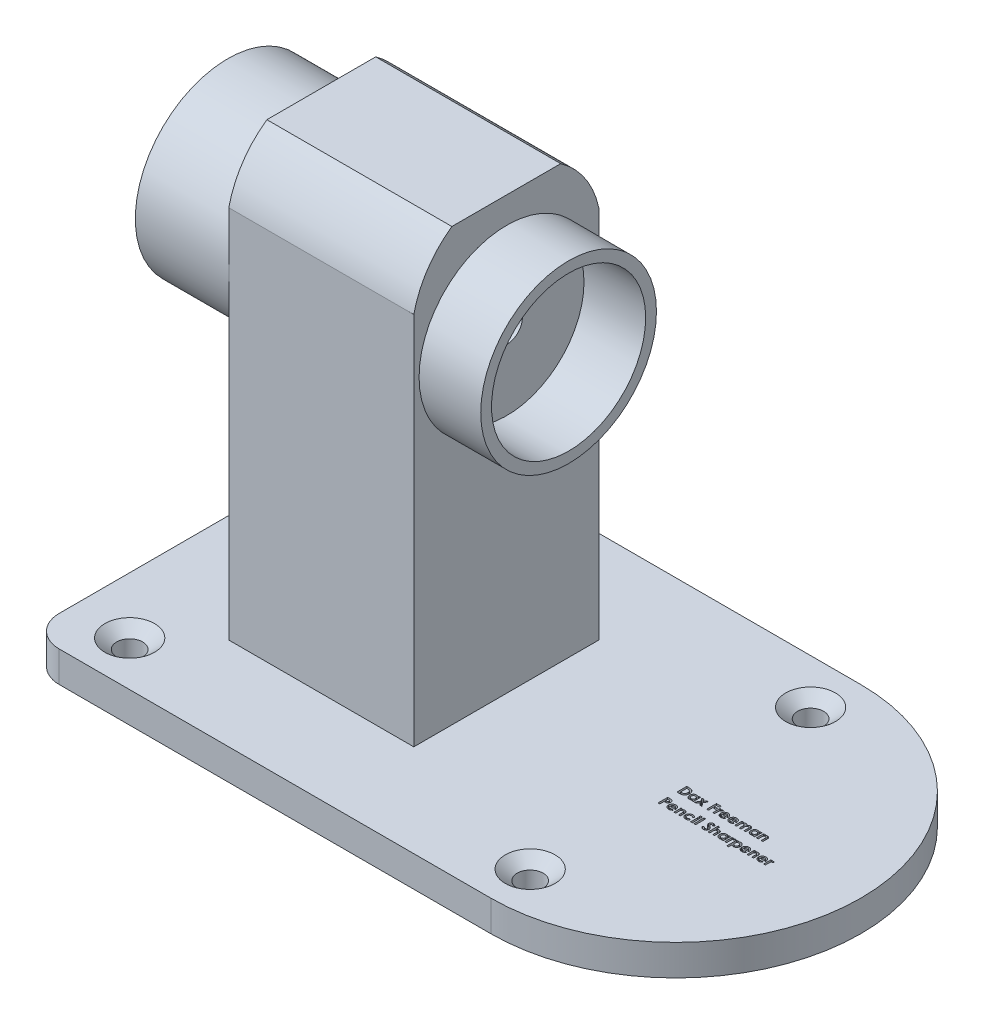
SolidWorks part; units mm, degrees
ref_plane "Front Plane" through (0, 0, 0) normal (0, 0, 1) x (1, 0, 0)
ref_plane "Top Plane" through (0, 0, 0) normal (0, 1, 0) x (1, 0, 0)
ref_plane "Right Plane" through (0, 0, 0) normal (1, 0, 0) x (0, 0, -1)
sketch "Sketch1" plane through (0, 0, 0) normal (0, 1, 0) x (1, 0, 0)
  line L0 (0, 0) -> (0, 120)
  line L1 (0, 120) -> (150, 120)
  line L2 (0, 0) -> (150, 0)
  arc A0 (150, 120) -> (150, 0) centre (150, 60) cw
  dimension "D1" = 150
  dimension "D2" = 150
  dimension "D3" = 120
extrude "Boss-Extrude1" add sketch "Sketch1" along normal blind 10
sketch "Sketch3" plane through (0, 0, 0) normal (0, 1, 0) x (1, 0, 0)
  line L1 (35, 30) -> (95, 30)
  line L2 (35, 30) -> (35, 90)
  line L3 (35, 90) -> (95, 90)
  line L4 (95, 30) -> (95, 90)
  line L5 (35, 30) -> (95, 90) construction
  line L6 (35, 90) -> (95, 30) construction
  point P0 (65, 60)
  dimension "D1" = 60
  dimension "D2" = 60
  dimension "D3" = 35
extrude "Boss-Extrude3" add sketch "Sketch3" along normal blind 150
sketch "Sketch4" plane through (0, 0, 0) normal (1, 0, 0) x (0, 0, -1)
  line L1 (30, 10) -> (90, 10)
  line L2 (30, 10) -> (30, 150)
  line L3 (30, 150) -> (90, 150)
  line L4 (90, 10) -> (90, 150)
  arc A0 (60, 155.577) -> (90, 131.449) centre (60, 124.8625) cw
  arc A1 (60, 155.577) -> (30, 131.449) centre (60, 124.8625) ccw
  dimension "D1" = 30.7145
  dimension "D2" = 124.8625
  dimension "D3" = 155.577
  dimension "D4" = 60
extrude "Cut-Extrude1" cut sketch "Sketch4" along normal blind 310 contours A1 L3 L2 | L3 A0 L4
ref_plane "Plane1" through (35, 0, 0) normal (1, 0, 0) x (0, 0, -1)
sketch "Sketch5" plane through (35, 0, 0) normal (1, 0, 0) x (0, 0, -1)
  circle A0 centre (60.2138, 112.9558) radius 30
  dimension "D1" = 60
  dimension "D2" = 60.2138
  dimension "D3" = 112.9558
extrude "Boss-Extrude5" add sketch "Sketch5" against normal blind 38
sketch "Sketch6" plane through (35, 0, 0) normal (1, 0, 0) x (0, 0, -1)
  circle A0 centre (60.2138, 112.9558) radius 5
  dimension "D1" = 10
extrude "Cut-Extrude2" cut sketch "Sketch6" against normal blind 81 and the other way blind 113
ref_plane "Plane2" through (95, 0, 0) normal (1, 0, 0) x (0, 0, -1)
sketch "Sketch7" plane through (95, 0, 0) normal (1, 0, 0) x (0, 0, -1)
  circle A0 centre (60.2138, 112.9558) radius 28.5
  circle A1 centre (60.2138, 112.9558) radius 25
  dimension "D1" = 57
  dimension "D2" = 50
extrude "Boss-Extrude6" add sketch "Sketch7" along normal blind 20
ref_plane "Plane3" through (115, 0, 0) normal (1, 0, 0) x (0, 0, -1)
chamfer "Chamfer1" distance 16 angle 25 1 edges at (-3, 112.9558, -90.2138)
fillet "Fillet1" radius 10 2 edges at (0, 5, -120) (0, 5, 0)
sketch "Sketch9" plane through (0, 10, 0) normal (0, 1, 0) x (1, 0, 0)
  text T0 "<b>Dax Freeman</b>\r\n<b>Pencil Sharpener</b>\r\n"
  dimension "D1" = 60
  dimension "D2" = 150
extrude "Cut-Extrude3" cut sketch "Sketch9" against normal blind 5
hole_wizard "CSK for 5/16 Flat Head Machine Screw (100)1" positions "Sketch11" profile "Sketch10" countersink size "5/16" standard "ANSI Inch" end condition through all
sketch "Sketch11" plane through (0, 10, 0) normal (0, 1, 0) x (1, 0, 0)
  point P0 (18.3249, 105.4767)
  point P2 (18.3249, 14.5233)
  point P4 (148.2277, 105.4767)
  point P6 (148.2277, 14.5233)
sketch "Sketch10" plane through (18.3249, 10, -105.4767) normal (1, 0, 0) x (0, 0, 1)
  line L0 (0, 0) -> (0, 10)
  line L1 (0, 10) -> (4.2164, 10)
  line L2 (4.2164, 10) -> (4.2164, 3.2289)
  line L3 (4.2164, 3.2289) -> (8.0645, 0)
  line L5 (8.0645, 0) -> (0, 0)
  line L6 (-4.2164, 3.2289) -> (-8.0645, 0) construction
  line L11 (0, -6.35) -> (0, 107.95) construction
  dimension "Thru Hole Dia." = 8.4328
  dimension "Thru Hole Depth" = 10
  dimension "Near C'Sink Dia." = 16.129
  dimension "Near C'Sink Angle" = 100
